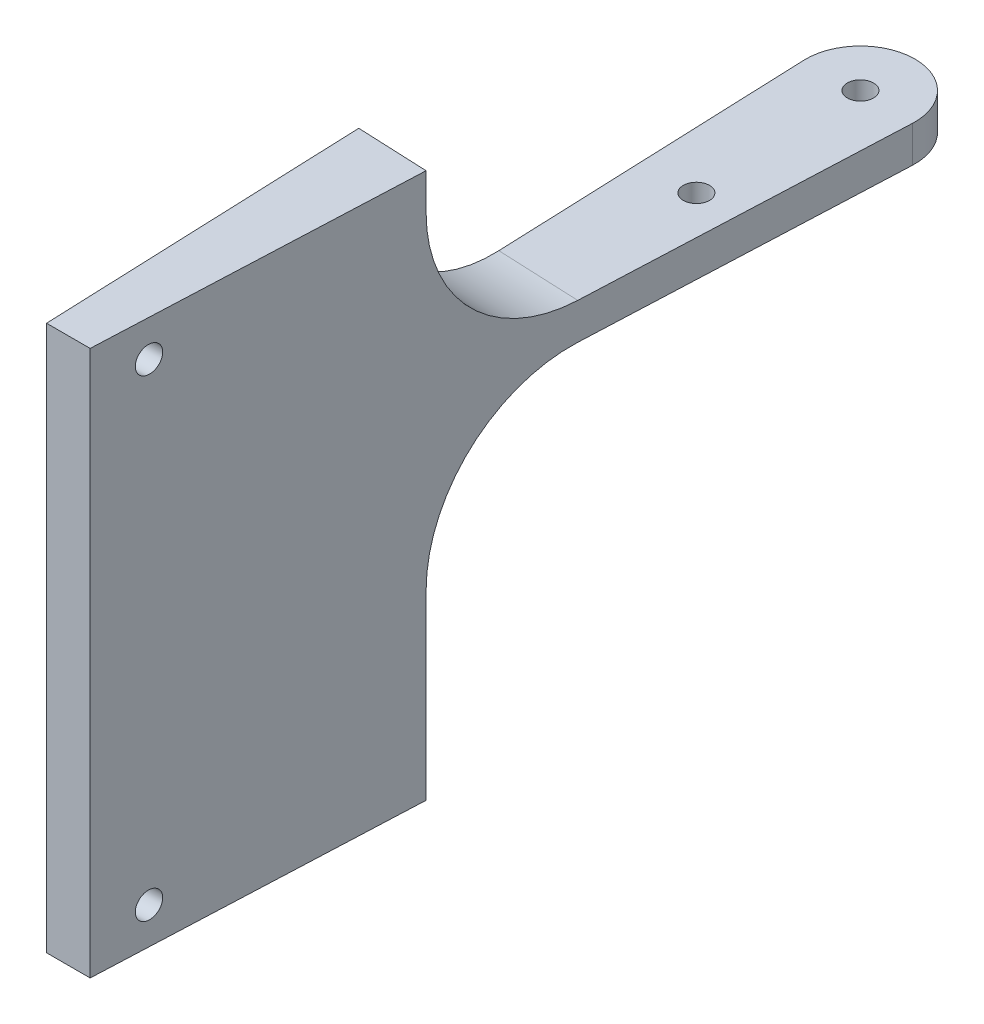
SolidWorks part; units mm, degrees
ref_plane "Front" through (0, 0, 0) normal (0, 0, 1) x (1, 0, 0)
ref_plane "Top" through (0, 0, 0) normal (0, 1, 0) x (1, 0, 0)
ref_plane "Right" through (0, 0, 0) normal (1, 0, 0) x (0, 0, -1)
sketch "Sketch1" plane through (0, 0, 0) normal (0, 1, 0) x (1, 0, 0)
  line L0 (-4.2443, -7.7934) -> (0, -116.2)
  line L1 (0, 0) -> (6, 0)
  line L2 (0, 0) -> (0, -116.2)
  line L3 (0, -116.2) -> (6, -116.2)
  line L4 (6, 0) -> (6, -116.2)
  line L5 (0, -116.2) -> (0, -14.2593)
  line L6 (0, -14.2593) -> (-4.2443, -7.7934)
  line L7 (10.7428, -7.8279) -> (6, -116.2)
  line L8 (6, -116.2) -> (6, -14.4776)
  line L9 (6, -14.4776) -> (10.7428, -7.8279)
  circle A0 centre (3.25, -7.5) radius 7.5
  dimension "D3" = 15
  dimension "D1" = 6
  dimension "D2" = 116.2
  dimension "D4" = 2.75
extrude "Boss-Extrude1" add sketch "Sketch1" along normal blind 5 contours L2 A0 L6 | L9 A0 L4 | L4 A0 L2 | A0 L0 L2 | A0 L4 L7 | A0 L2 L3 L4 | L9 A0 | L6 A0
sketch "Sketch2" plane through (0, 5, 0) normal (0, 1, 0) x (1, 0, 0)
  line L0 (-1.7499, -71.5034) -> (7.9376, -71.9274)
  line L1 (-4.2443, -7.7934) -> (0, -116.2) construction
  line L2 (10.7428, -7.8279) -> (6, -116.2) construction
  line L3 (7.9376, -71.9274) -> (6, -116.2)
  line L4 (6, -116.2) -> (0, -116.2)
  line L5 (0, -116.2) -> (-1.7499, -71.5034)
extrude "Boss-Extrude2" add sketch "Sketch2" along normal blind 25 and the other way blind 50
fillet "Fillet1" radius 20 2 edges at (3.0938, 0, 71.7154) (3.0938, 5, 71.7154)
sketch "Sketch3" plane through (0, 5, 0) normal (0, 1, 0) x (1, 0, 0)
  circle A0 centre (3.25, -7.5) radius 1.8
  circle A1 centre (4.1694, -30.982) radius 1.8
extrude "Cut-Extrude1" cut sketch "Sketch3" against normal blind 19
sketch "Sketch4" plane through (-4.5424, 0, 0.1778) normal (-0.9992, 0, 0.0391) x (0.0391, 0, 0.9992)
  line L0 (116.111, 30) -> (116.111, -45) construction
  line L1 (71.3802, -45) -> (116.111, -45) construction
  line L2 (71.3802, 30) -> (116.111, 30) construction
  circle A0 centre (108.611, -40) radius 1.8
  circle A1 centre (108.611, 25) radius 1.8
  dimension "D1" = 7.5
  dimension "D2" = 7.5
  dimension "D3" = 5
  dimension "D4" = 5
extrude "Cut-Extrude2" cut sketch "Sketch4" against normal blind 10
